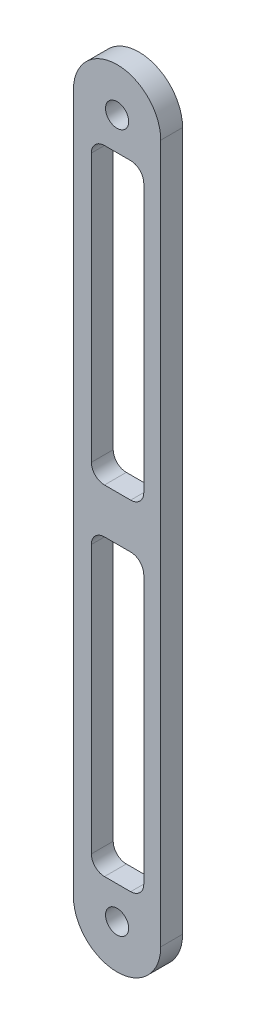
SolidWorks part; units mm, degrees
ref_plane "前视基准面" through (0, 0, 0) normal (0, 0, 1) x (1, 0, 0)
ref_plane "上视基准面" through (0, 0, 0) normal (0, 1, 0) x (1, 0, 0)
ref_plane "右视基准面" through (0, 0, 0) normal (1, 0, 0) x (0, 0, -1)
sketch "草图1" plane through (0, 0, 0) normal (0, 0, 1) x (1, 0, 0)
  line L0 (6.112, 5.163) -> (6.112, 72.5)
  line L1 (-10, 80) -> (10, 80) construction
  line L2 (-10, 80) -> (-10, -80)
  line L3 (-10, -80) -> (10, -80) construction
  line L4 (10, 80) -> (10, -80)
  line L5 (0, -80) -> (0, 80) construction
  line L6 (-10, 0) -> (10, 0) construction
  line L7 (6.112, 72.5) -> (-5.888, 72.5)
  line L8 (6.112, -72.5) -> (-5.888, -72.5)
  line L9 (-5.888, 72.5) -> (-5.888, 5.163)
  line L10 (6.112, 5.163) -> (-5.888, 5.163)
  line L11 (-5.888, -5.1372) -> (-5.888, -72.5)
  line L12 (6.112, -72.5) -> (6.112, -5.1372)
  line L13 (6.112, -5.1372) -> (-5.888, -5.1372)
  arc A0 (10, 80) -> (-10, 80) centre (0, 80) ccw
  arc A1 (-10, -80) -> (10, -80) centre (0, -80) ccw
  circle A2 centre (0, 80) radius 2.65
  circle A3 centre (0, -80) radius 2.65
  point P0 (0, 0)
  point P5 (0, 0)
  point P6 (0, 0)
  point P14 (6.112, -72.5)
  point P17 (-5.888, 72.5)
  point P18 (-5.888, -5.1372)
  point P20 (6.112, 72.5)
  dimension "D3" = 5.3
  dimension "D4" = 5.3
  dimension "D1" = 160
  dimension "D2" = 20
  dimension "D6" = 12
extrude "凸台-拉伸1" add sketch "草图1" along normal blind 5
fillet "圆角1" radius 3 8 edges at (-5.888, -72.5, 2.5) (6.112, -72.5, 2.5) (6.112, -5.1372, 2.5) (-5.888, -5.1372, 2.5) (6.112, 5.163, 2.5) (-5.888, 5.163, 2.5) (6.112, 72.5, 2.5) (-5.888, 72.5, 2.5)
